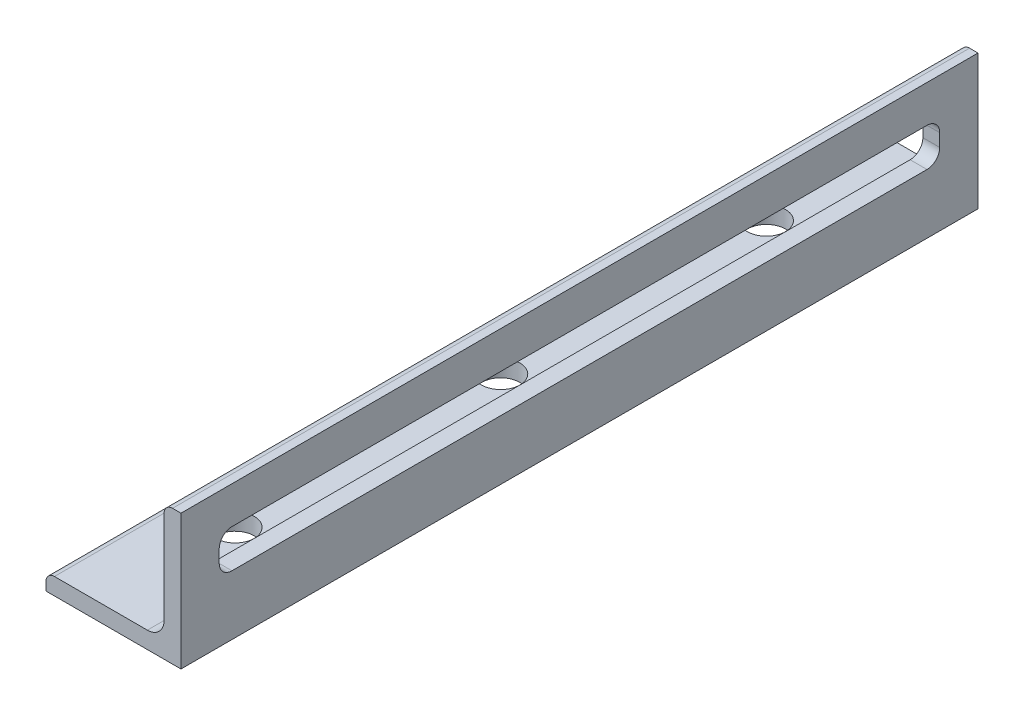
SolidWorks part; units mm, degrees
ref_plane "Front Plane" through (0, 0, 0) normal (0, 0, 1) x (1, 0, 0)
ref_plane "Top Plane" through (0, 0, 0) normal (0, 1, 0) x (1, 0, 0)
ref_plane "Right Plane" through (0, 0, 0) normal (1, 0, 0) x (0, 0, -1)
sketch "Sketch0" plane through (0, 0, 0) normal (0, 0, 1) x (1, 0, 0)
  line L0 (-6.35, -6.35) -> (6.35, -6.35)
  line L1 (6.35, -6.35) -> (6.35, 6.35)
  line L2 (6.35, 0) -> (0, 0) construction
  line L3 (0, 0) -> (0, -6.35) construction
  line L4 (4.7625, -3.1877) -> (4.7625, 6.35) construction
  line L5 (3.1877, -4.7625) -> (-6.35, -4.7625) construction
  arc A0 (4.7625, -3.1877) -> (3.1877, -4.7625) centre (3.1877, -3.1877) cw
  point P3 (4.3013, -4.3013)
  dimension "Inside Corner Radius" = 1.5748
  dimension "Outside Height" = 12.7
  dimension "Inside Height" = 11.1125
  dimension "Inside Width" = 11.1125
  dimension "Wall Thickness" = 1.5875
  dimension "D1" = 1.5875
  dimension "Outside Width" = 12.7
sketch "Sketch1" plane through (0, 0, 0) normal (1, 0, 0) x (0, 0, -1)
  line L0 (304.8, 0) -> (-304.8, 0)
  point P4 (0, 0)
  dimension "Length" = 609.6
sketch "Sketch2" plane through (0, 0, 0) normal (0, 0, 1) x (1, 0, 0)
  line L0 (-6.35, -6.35) -> (6.35, -6.35)
  line L1 (6.35, -6.35) -> (6.35, 6.35)
  line L2 (6.35, 6.35) -> (4.7625, 6.35) construction
  line L3 (4.7625, 5.5563) -> (4.7625, -3.1877)
  line L4 (3.1877, -4.7625) -> (-5.5563, -4.7625)
  line L5 (-6.35, -6.35) -> (-6.35, -4.7625) construction
  line L6 (5.5563, 6.35) -> (6.35, 6.35)
  line L7 (-6.35, -5.5563) -> (-6.35, -6.35)
  line L8 (6.35, 0) -> (0, 0) construction
  line L9 (0, 0) -> (0, -6.35) construction
  arc A0 (4.7625, 5.5563) -> (5.5563, 6.35) centre (5.5563, 5.5563) cw
  arc A1 (-6.35, -5.5563) -> (-5.5563, -4.7625) centre (-5.5563, -5.5563) cw
  arc A2 (4.7625, -3.1877) -> (3.1877, -4.7625) centre (3.1877, -3.1877) cw
  dimension "Inside Radius" = 1.5748
  dimension "Height" = 12.7
  dimension "Width" = 12.7
  dimension "Thickness" = 1.5875
extrude "Boss-Extrude1" add sketch "Sketch2" along normal mid plane 75
sketch "Break Locations" plane through (0, 0, 0) normal (1, 0, 0) x (0, 0, -1)
  line L0 (-24.546, 0) -> (24.546, 0)
  line L1 (-37.5, -6.35) -> (-37.5, 6.35) construction
  line L2 (37.5, -6.35) -> (37.5, 6.35) construction
  point P0 (-26.705, 0)
  point P1 (26.705, 0)
  point P10 (0, 0)
  point P11 (24.546, 0)
  point P13 (-24.546, 0)
  dimension "D1" = 10.795
  dimension "D2" = 10.795
  dimension "D3" = 12.954
sketch "Sketch3" plane through (0, -4.7625, 0) normal (0, 1, 0) x (1, 0, 0)
  line L0 (-1.0623, 0) -> (-1.0623, -25) construction
  line L2 (-1.0623, 25) -> (-1.0623, 0) construction
  line L3 (3.1877, 0) -> (-5.3123, 0) construction
  line L5 (3.1877, -37.5) -> (3.1877, 37.5) construction
  circle A0 centre (-1.0623, 25) radius 1.8
  circle A1 centre (-1.0623, -25) radius 1.8
  circle A2 centre (-1.0623, 0) radius 1.8
  point P6 (-1.0623, 0)
  dimension "ForwardMount" = 3.6
  dimension "D1" = 50
  dimension "D2" = 8.5
extrude "Cut-Extrude1" cut sketch "Sketch3" against normal through all
sketch "Sketch4" plane through (4.7625, 0, 0) normal (-1, 0, 0) x (0, 0, 1)
  line L0 (37.5, 5.5563) -> (-37.5, 5.5563) construction
  line L1 (-32.7, 2.8563) -> (32.7, 2.8563)
  line L2 (-33.9, 1.6563) -> (-33.9, 0.4563)
  line L3 (-32.7, -0.7437) -> (32.7, -0.7437)
  line L4 (33.9, 1.6563) -> (33.9, 0.4563)
  line L5 (-33.9, 2.8563) -> (33.9, -0.7437) construction
  line L6 (-33.9, -0.7437) -> (33.9, 2.8563) construction
  line L7 (-37.5, 5.5563) -> (-37.5, -3.1877) construction
  line L8 (37.5, 5.5563) -> (37.5, -3.1877) construction
  arc A0 (33.9, 0.4563) -> (32.7, -0.7437) centre (32.7, 0.4563) cw
  arc A1 (32.7, 2.8563) -> (33.9, 1.6563) centre (32.7, 1.6563) cw
  arc A2 (-32.7, -0.7437) -> (-33.9, 0.4563) centre (-32.7, 0.4563) cw
  arc A3 (-32.7, 2.8563) -> (-33.9, 1.6563) centre (-32.7, 1.6563) ccw
  point P0 (0, 1.0563)
  dimension "D5" = 1.2
  dimension "D1" = 4.5
  dimension "D2" = 3.6
  dimension "D3" = 3.6
  dimension "D4" = 3.6
extrude "Cut-Extrude2" cut sketch "Sketch4" against normal through all
ref_point "Point2"
ref_point "Point4"
equation "\"D1@Break Locations\" = .85 * \"Height@Sketch2\""
equation "\"D2@Break Locations\"=\"D1@Break Locations\""
equation "\"Thickness@Sketch2\" = \"Wall Thickness@Sketch0\""
equation "\"Height@Sketch2\" = \"Outside Height@Sketch0\""
equation "\"Width@Sketch2\" = \"Outside Width@Sketch0\""
equation "\"Inside Radius@Sketch2\" = \"Inside Corner Radius@Sketch0\""
equation "\"D3@Break Locations\"=\"D2@Break Locations\"*1.2"
equation "\"D1@Sketch0\"=\"Wall Thickness@Sketch0\""
equation "\"HoleDiameter\"=3.6"
equation "\"ForwardMount@Sketch3\" = \"HoleDiameter\""
equation "\"D5@Sketch4\"=\"D4@Sketch4\"/3"
equation "\"D3@Sketch4\"=\"D4@Sketch4\""
equation "\"D2@Sketch4\"=\"D3@Sketch4\""
